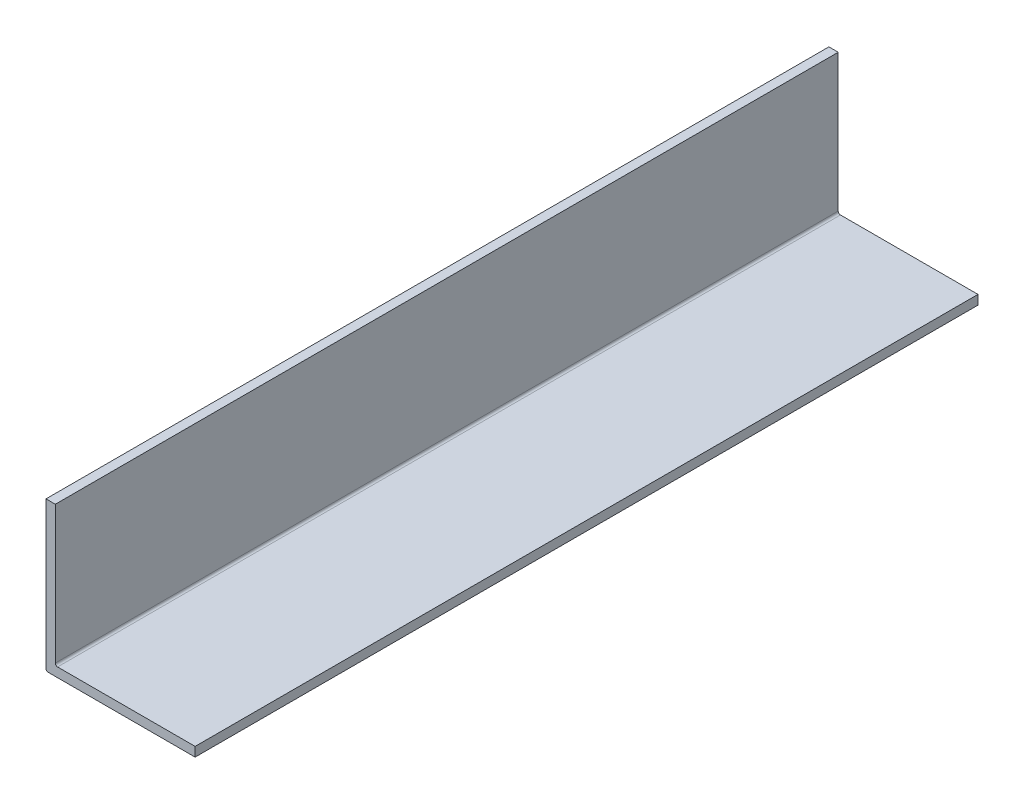
SolidWorks part; units mm, degrees
ref_plane "Front Plane" through (0, 0, 0) normal (0, 0, 1) x (1, 0, 0)
ref_plane "Top Plane" through (0, 0, 0) normal (0, 1, 0) x (1, 0, 0)
ref_plane "Right Plane" through (0, 0, 0) normal (1, 0, 0) x (0, 0, -1)
sketch "Sketch1" plane through (0, 0, 0) normal (0, 0, 1) x (1, 0, 0)
  line L0 (3.175, 50.8) -> (3.175, 3.937)
  line L1 (0.762, 0) -> (50.8, 0)
  line L2 (0, 0.762) -> (0, 50.8)
  line L3 (0, 50.8) -> (3.175, 50.8)
  line L4 (50.8, 0) -> (50.8, 3.175)
  line L5 (3.937, 3.175) -> (50.8, 3.175)
  arc A0 (0, 0.762) -> (0.762, 0) centre (0.762, 0.762) ccw
  arc A1 (3.175, 3.937) -> (3.937, 3.175) centre (3.937, 3.937) ccw
  point P10 (0, 0)
  dimension "D5" = 0.762
  dimension "D6" = 0.762
  dimension "D1" = 50.8
  dimension "D2" = 50.8
  dimension "D3" = 3.175
  dimension "D4" = 3.175
extrude "Boss-Extrude1" add sketch "Sketch1" along normal blind 266.7
